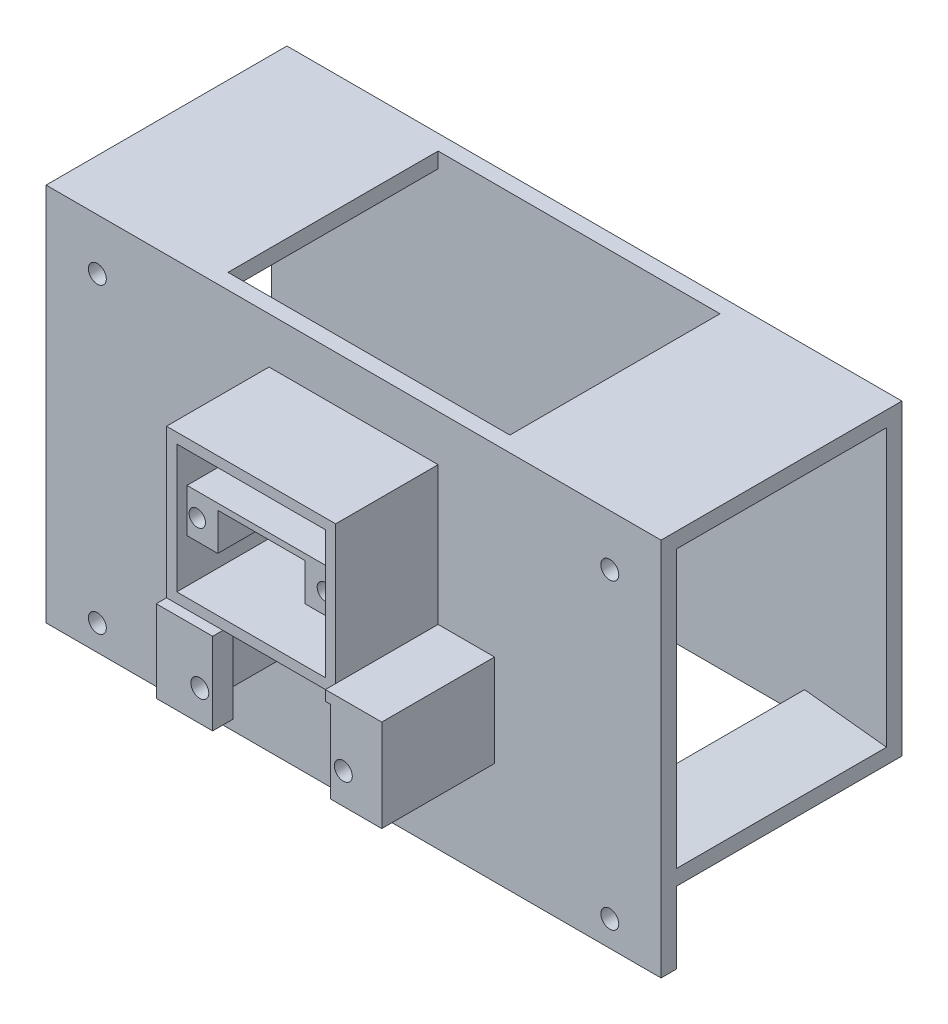
SolidWorks part; units mm, degrees
ref_plane "前视基准面" through (0, 0, 0) normal (0, 0, 1) x (1, 0, 0)
ref_plane "上视基准面" through (0, 0, 0) normal (0, 1, 0) x (1, 0, 0)
ref_plane "右视基准面" through (0, 0, 0) normal (1, 0, 0) x (0, 0, -1)
sketch "草图1" plane through (0, 0, 0) normal (0, 0, -1) x (1, 0, 0)
  line L4 (-60, 30) -> (60, -30) construction
  line L5 (-60, -30) -> (60, -30)
  line L6 (-60, -30) -> (-60, 30)
  line L7 (-60, 30) -> (60, 30)
  line L8 (60, -30) -> (60, 30)
  dimension "D1" = 120
  dimension "D2" = 60
extrude "凸台-拉伸1" add sketch "草图1" along normal blind 47
shell "抽壳2" thickness 3
sketch "草图2" plane through (0, 30, 45) normal (0, -1, 0) x (-1, 0, 0)
  line L0 (0, 92) -> (0, 68.5) construction
  line L1 (-60, 92) -> (60, 92) construction
  line L2 (0, 68.5) -> (-60, 68.5) construction
  line L5 (-60, 92) -> (-60, 45) construction
  line L6 (60, 89) -> (-60, 89) construction
  line L7 (-27.5, 89) -> (27.5, 89)
  line L8 (-27.5, 89) -> (-27.5, 48)
  line L9 (-27.5, 48) -> (27.5, 48)
  line L10 (27.5, 89) -> (27.5, 48)
  line L11 (-27.5, 89) -> (27.5, 48) construction
  line L12 (-27.5, 48) -> (27.5, 89) construction
  point P15 (-60, 68.5)
  dimension "D2" = 55
extrude "切除-拉伸1" cut sketch "草图2" along normal up to surface (3 mm away) up to face at (0, 27, -23.5)
sketch "草图5" plane through (0, -30, 0) normal (0, -1, 0) x (1, 0, 0)
  line L0 (0, 0) -> (0, -23.5) construction
  line L1 (-44, -44) -> (44, -44)
  line L2 (-44, -44) -> (-44, -3)
  line L3 (-44, -3) -> (44, -3)
  line L4 (44, -44) -> (44, -3)
  line L5 (-44, -44) -> (44, -3) construction
  line L6 (-44, -3) -> (44, -44) construction
  line L7 (60, 0) -> (-60, 0) construction
  line L8 (0, -23.5) -> (-60, -23.5) construction
  line L9 (-60, -47) -> (-60, 0) construction
  line L11 (27.5, -3) -> (60, -3) construction
  point P0 (0, -23.5)
  dimension "D1" = 88
extrude "切除-拉伸3" cut sketch "草图5" against normal blind 10
sketch "草图6" plane through (0, 0, 0) normal (0, 0, 1) x (1, 0, 0)
  line L6 (0, 30) -> (0, -18) construction
  line L8 (-60, 30) -> (60, 30) construction
  line L9 (27.5, 27) -> (60, 27) construction
  circle A1 centre (0, -18) radius 2.5
  dimension "D1" = 5
  dimension "D2" = 45
  dimension "D3" = 48
extrude "切除-拉伸4" cut sketch "草图6" against normal through all
sketch "草图8" plane through (0, 0, -44) normal (0, 0, -1) x (-1, 0, 0)
  line L0 (-60, -27) -> (-44, -25.2705)
  line L1 (-44, -25.2705) -> (-44, -30)
  line L2 (-60, -30) -> (60, -30) construction
  line L3 (-44, -30) -> (-60, -30)
  line L4 (-60, -30) -> (-60, -27)
  line L6 (-60, 30) -> (-60, -30) construction
  line L7 (-44, -27) -> (-44, -30) construction
  circle A0 centre (0, -18) radius 1.3759 construction
  circle A1 centre (0, -18) radius 2.5 construction
extrude "凸台-拉伸4" add sketch "草图8" against normal up to surface (41 mm away)
mirror "镜向1" about plane through (0, 0, 0) normal (1, 0, 0) of "凸台-拉伸4"
sketch "草图9" plane through (0, 0, 0) normal (0, 0, 1) x (1, 0, 0)
  line L0 (0, 6.5) -> (0, 30) construction
  line L1 (-8.5, 19) -> (8.5, 19)
  line L2 (-8.5, 19) -> (-8.5, -6)
  line L3 (-8.5, -6) -> (8.5, -6)
  line L4 (8.5, 19) -> (8.5, -6)
  line L5 (-8.5, 19) -> (8.5, -6) construction
  line L6 (-8.5, -6) -> (8.5, 19) construction
  line L7 (-60, 30) -> (60, 30) construction
  point P0 (0, 6.5)
  dimension "D1" = 17
  dimension "D2" = 25
  dimension "D3" = 11
extrude "切除-拉伸5" cut sketch "草图9" against normal up to next
sketch "草图10" plane through (0, 0, 0) normal (0, 0, 1) x (1, 0, 0)
  line L0 (0, 19) -> (0, 6.5) construction
  line L3 (-10.5, -8) -> (10.5, -8)
  line L5 (-16.5, 21) -> (16.5, 21)
  line L6 (-8.5, 19) -> (8.5, 19) construction
  line L11 (8.5, -6) -> (-8.5, -6) construction
  line L12 (-8.5, -6) -> (-8.5, 19) construction
  line L13 (8.5, 19) -> (-8.5, 19) construction
  line L14 (0, 6.5) -> (-8.5, 6.5) construction
  line L15 (-8.5, 19) -> (-8.5, -6) construction
  line L22 (-8.5, 11) -> (14.5, 11)
  line L23 (-8.5, 9.8) -> (8.5, 9.8)
  line L24 (8.5, 9.8) -> (8.5, 2.5)
  line L25 (-8.5, 9.8) -> (-8.5, 2.5)
  line L26 (8.5, 19) -> (8.5, -6) construction
  line L27 (-16.5, 21) -> (-16.5, -8)
  line L28 (-16.5, -8) -> (-10.5, -8)
  line L30 (16.5, 21) -> (16.5, -8)
  line L31 (16.5, -8) -> (10.5, -8)
  line L34 (-14.5, 19) -> (14.5, 19)
  line L35 (-14.5, 19) -> (-14.5, 11)
  line L36 (-14.5, 11) -> (-8.5, 11)
  line L38 (14.5, 19) -> (14.5, 11)
  line L40 (-8.5, 2.5) -> (-14.5, 2.5)
  line L41 (-14.5, 2.5) -> (-14.5, -6)
  line L42 (-14.5, -6) -> (14.5, -6)
  line L43 (8.5, 2.5) -> (14.5, 2.5)
  line L44 (14.5, 2.5) -> (14.5, -6)
  line L45 (-14.5, 11) -> (-14.5, 2.5) construction
  line L48 (-14.5, 6.75) -> (-22.7649, 6.75) construction
  circle A1 centre (-12.5, 6.5) radius 1.6
  circle A3 centre (12.5, 6.5) radius 1.6
  point P0 (0, 6.5)
  point P5 (0, 6.5)
  dimension "D3" = 3.2
  dimension "D4" = 25
  dimension "D2" = 4
  dimension "D5" = 1.2
  dimension "D6" = 4
  dimension "D7" = 2
  dimension "D8" = 2
  dimension "D9" = 2
  dimension "D10" = 2
  dimension "D11" = 8
  dimension "D12" = 25
  dimension "D13" = 4
  dimension "D14" = 29
extrude "凸台-拉伸5" add sketch "草图10" along normal blind 18
sketch "草图13" plane through (0, 0, 18) normal (0, 0, 1) x (1, 0, 0)
  line L1 (-14.5, 19) -> (14.5, 19)
  line L2 (-14.5, 19) -> (-14.5, -6)
  line L3 (-14.5, -6) -> (14.5, -6)
  line L4 (-16.5, -8) -> (16.5, -8)
  line L5 (16.5, -8) -> (16.5, 21)
  line L6 (16.5, 21) -> (-16.5, 21)
  line L7 (-16.5, 21) -> (-16.5, -8)
  line L8 (-16.5, -8) -> (16.5, -8)
  line L9 (16.5, -8) -> (16.5, 21)
  line L10 (16.5, 21) -> (-16.5, 21)
  line L11 (-16.5, 21) -> (-16.5, -8)
  line L12 (14.5, 19) -> (14.5, -6)
  dimension "D1" = 0
extrude "凸台-拉伸6" add sketch "草图13" along normal blind 2
sketch "草图14" plane through (0, 0, 0) normal (0, 0, 1) x (1, 0, 0)
  line L0 (-5.5, -16) -> (17.5, -16) construction
  line L1 (-15.5, -8) -> (-5.5, -8)
  line L2 (-15.5, -8) -> (-15.5, -24)
  line L3 (-15.5, -24) -> (-5.5, -24)
  line L4 (-5.5, -8) -> (-5.5, -24)
  line L5 (17.5, -8) -> (27.5, -8)
  line L6 (17.5, -8) -> (17.5, -24)
  line L7 (17.5, -24) -> (27.5, -24)
  line L8 (27.5, -8) -> (27.5, -24)
  line L9 (-8, -18) -> (0, -18) construction
  line L10 (6, -16) -> (6, -23.5101) construction
  line L11 (-16.5, -8) -> (16.5, -8) construction
  circle A1 centre (-8, -18) radius 1.75
  circle A2 centre (20, -18) radius 1.75
  dimension "D5" = 3.5
  dimension "D1" = 8
  dimension "D2" = 28
  dimension "D3" = 23
  dimension "D4" = 10
  dimension "D6" = 6
extrude "凸台-拉伸7" add sketch "草图14" along normal blind 22
sketch "草图15" plane through (0, 0, 0) normal (0, 0, 1) x (1, 0, 0)
  circle A0 centre (0, -18) radius 10.5
  dimension "D1" = 21
extrude "切除-拉伸7" cut sketch "草图15" along normal blind 12
sketch "草图17" plane through (0, 0, 12) normal (0, 0, -1) x (-1, 0, 0)
  line L5 (5.5, -9.0557) -> (5.5, -24)
  line L6 (5.5, -24) -> (8.6168, -24)
  line L9 (5.5, -9.0557) -> (5.5, -24)
  line L10 (5.5, -24) -> (8.6168, -24)
  arc A3 (8.6168, -24) -> (5.5, -9.0557) centre (0, -18) ccw
  arc A5 (8.6168, -24) -> (5.5, -9.0557) centre (0, -18) ccw
  dimension "D1" = 0
extrude "切除-拉伸8" cut sketch "草图17" against normal offset from surface (6 mm away) 4 up to face at (-10.5, -16, 22)
sketch "草图19" plane through (0, 0, 0) normal (0, 0, 1) x (1, 0, 0)
  line L0 (-15.5, -24) -> (-8.6168, -24) construction
  line L1 (-11, -24) -> (23, -24)
  line L2 (-11, -24) -> (-11, -8)
  line L3 (-11, -8) -> (23, -8)
  line L4 (23, -24) -> (23, -8)
  line L7 (-5.5, -8) -> (16.5, -8) construction
  line L8 (-8, -18) -> (20, -18) construction
  line L9 (6, -18) -> (6, -24) construction
  dimension "D1" = 34
extrude "切除-拉伸9" cut sketch "草图19" along normal up to surface (18 mm away) up to face at (-6.25, -18, 18)
sketch "草图16" plane through (0, 0, 0) normal (0, 0, 1) x (1, 0, 0)
  line L0 (-14.5, -6) -> (14.5, -6) construction
  line L1 (-16.5, -8) -> (-15.5, -8)
  line L2 (-16.5, -8) -> (-16.5, -24)
  line L3 (-16.5, -24) -> (-15.5, -24)
  line L4 (-15.5, -8) -> (-15.5, -24)
  line L5 (16.5, -8) -> (27.5, -8)
  line L6 (16.5, -8) -> (16.5, -6)
  line L7 (16.5, -6) -> (27.5, -6)
  line L8 (27.5, -8) -> (27.5, -6)
  line L10 (27.5, -24) -> (27.5, -8) construction
extrude "凸台-拉伸8" add sketch "草图16" along normal up to surface (22 mm away) up to face at (-10.5, -16, 22)
sketch "草图20" plane through (0, 0, -3) normal (0, 0, -1) x (-1, 0, 0)
  line L1 (-15.5, 9.5) -> (-9.5, 9.5)
  line L2 (-15.5, 9.5) -> (-15.5, 3.5)
  line L3 (-15.5, 3.5) -> (-9.5, 3.5)
  line L4 (-9.5, 9.5) -> (-9.5, 3.5)
  line L5 (-15.5, 9.5) -> (-9.5, 3.5) construction
  line L6 (-15.5, 3.5) -> (-9.5, 9.5) construction
  line L7 (15.5, 9.5) -> (9.5, 9.5)
  line L8 (15.5, 9.5) -> (15.5, 3.5)
  line L9 (15.5, 3.5) -> (9.5, 3.5)
  line L10 (9.5, 9.5) -> (9.5, 3.5)
  line L11 (15.5, 9.5) -> (9.5, 3.5) construction
  line L12 (15.5, 3.5) -> (9.5, 9.5) construction
  circle A4 centre (-12.5, 6.5) radius 1.6 construction
  circle A5 centre (12.5, 6.5) radius 1.6 construction
  point P0 (-12.5, 6.5)
  point P5 (12.5, 6.5)
  dimension "D2" = 6
extrude "切除-拉伸10" cut sketch "草图20" against normal offset from surface (11 mm away) 10 up to face at (14.1, 6.5, 18)
sketch "草图21" plane through (0, -30, 0) normal (0, -1, 0) x (1, 0, 0)
  line L0 (60, -47) -> (60, 0) construction
  line L1 (-60, 0) -> (60, 0)
  line L2 (-60, 0) -> (-60, -3)
  line L3 (-60, -3) -> (60, -3)
  line L4 (60, 0) -> (60, -3)
  line L5 (44, -3) -> (-44, -3) construction
extrude "凸台-拉伸9" add sketch "草图21" along normal blind 14
sketch "草图11" plane through (0, 0, 0) normal (0, 0, -1) x (-1, 0, 0)
  line L0 (0, 30) -> (0, -30) construction
  line L1 (60, 30) -> (-60, 30) construction
  line L2 (-60, -30) -> (60, -30) construction
  line L3 (60, -44) -> (-60, -44) construction
  circle A0 centre (-50, 20) radius 1.75
  circle A1 centre (50, 20) radius 1.75
  circle A2 centre (-50, -39) radius 1.75
  circle A3 centre (50, -39) radius 1.75
  dimension "D1" = 3.5
  dimension "D2" = 100
  dimension "D3" = 10
  dimension "D4" = 5
  dimension "D5" = 59
extrude "切除-拉伸6" cut sketch "草图11" along normal through all
sketch "草图22" plane through (0, 0, -47) normal (0, 0, -1) x (-1, 0, 0)
  line L0 (-28.3195, 2) -> (28.3195, 2) construction
  line L1 (-6.5519, 24.61) -> (9.2716, 24.61)
  line L2 (-6.5519, 24.61) -> (-6.5519, 5.4488)
  line L3 (-6.5519, 5.4488) -> (9.2716, 5.4488)
  line L4 (9.2716, 24.61) -> (9.2716, 5.4488)
  line L5 (0, -18) -> (0, 2) construction
  point P9 (0, 0)
  dimension "D1" = 19.1612
  dimension "D2" = 20
  dimension "D3" = 3.4488
